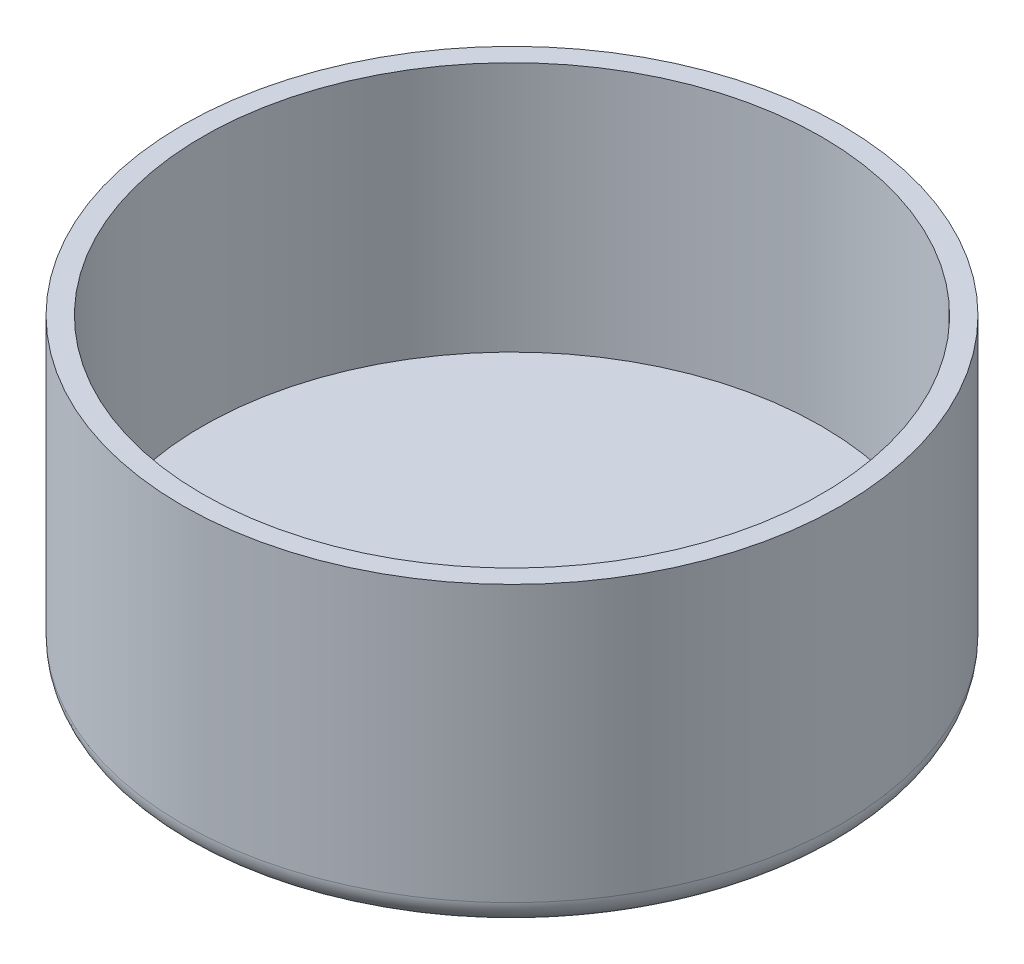
SolidWorks part; units mm, degrees
ref_plane "Front" through (0, 0, 0) normal (0, 0, 1) x (1, 0, 0)
ref_plane "Top" through (0, 0, 0) normal (0, 1, 0) x (1, 0, 0)
ref_plane "Right" through (0, 0, 0) normal (1, 0, 0) x (0, 0, -1)
sketch "Sketch1" plane through (0, 0, 0) normal (0, 1, 0) x (1, 0, 0)
  circle A0 centre (0, 0) radius 13.15
  dimension "D1" = 26.3
extrude "Boss-Extrude1" add sketch "Sketch1" along normal blind 2
sketch "Sketch2" plane through (0, 2, 0) normal (0, 1, 0) x (1, 0, 0)
  circle A0 centre (0, 0) radius 13.15 construction
  circle A1 centre (0, 0) radius 13.15
  circle A2 centre (0, 0) radius 12.35
  dimension "D1" = 0.8
extrude "Boss-Extrude2" add sketch "Sketch2" along normal blind 10
fillet "Fillet1" radius 1 1 edges at (0, 0, 13.15)
